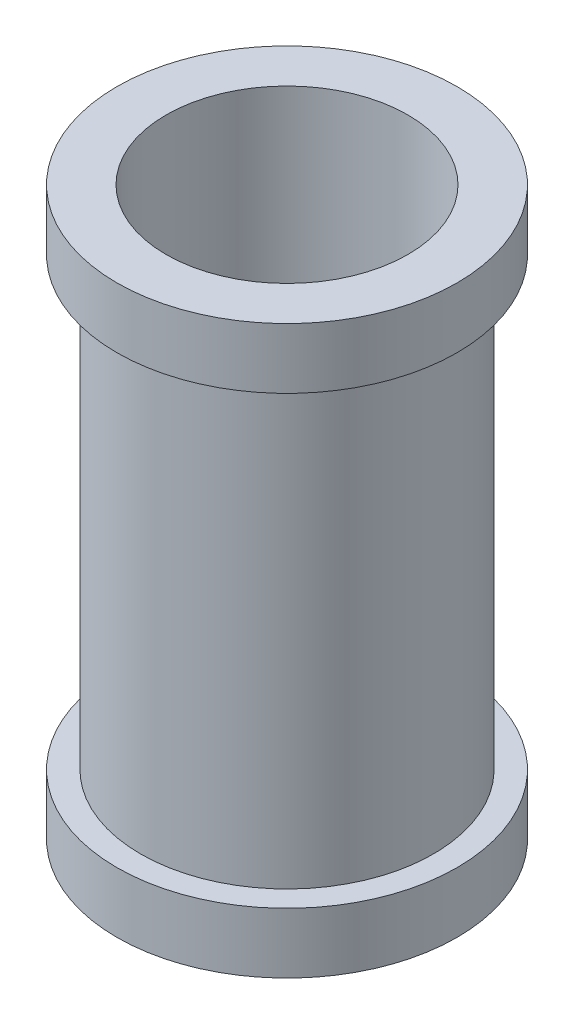
SolidWorks part; units mm, degrees
ref_plane "Front Plane" through (0, 0, 0) normal (0, 0, 1) x (1, 0, 0)
ref_plane "Top Plane" through (0, 0, 0) normal (0, 1, 0) x (1, 0, 0)
ref_plane "Right Plane" through (0, 0, 0) normal (1, 0, 0) x (0, 0, -1)
sketch "Sketch3" plane through (0, 0, 0) normal (0, 0, 1) x (1, 0, 0)
  line L0 (0, 0) -> (8.255, 0)
  line L1 (8.255, 0) -> (8.255, 10.16)
  line L2 (8.255, 10.16) -> (4.2862, 10.16)
  line L3 (4.2862, 10.16) -> (4.2862, 85.09)
  line L4 (8.255, 85.09) -> (4.2862, 85.09)
  line L5 (8.255, 85.09) -> (8.255, 95.25)
  line L6 (8.255, 95.25) -> (0, 95.25)
  line L7 (0, 95.25) -> (0, 0)
  line L9 (-20.32, 95.25) -> (-20.32, 0) construction
  dimension "D1" = 8.255
revolve "Revolve1" add sketch "Sketch3" angle 360 about L9
